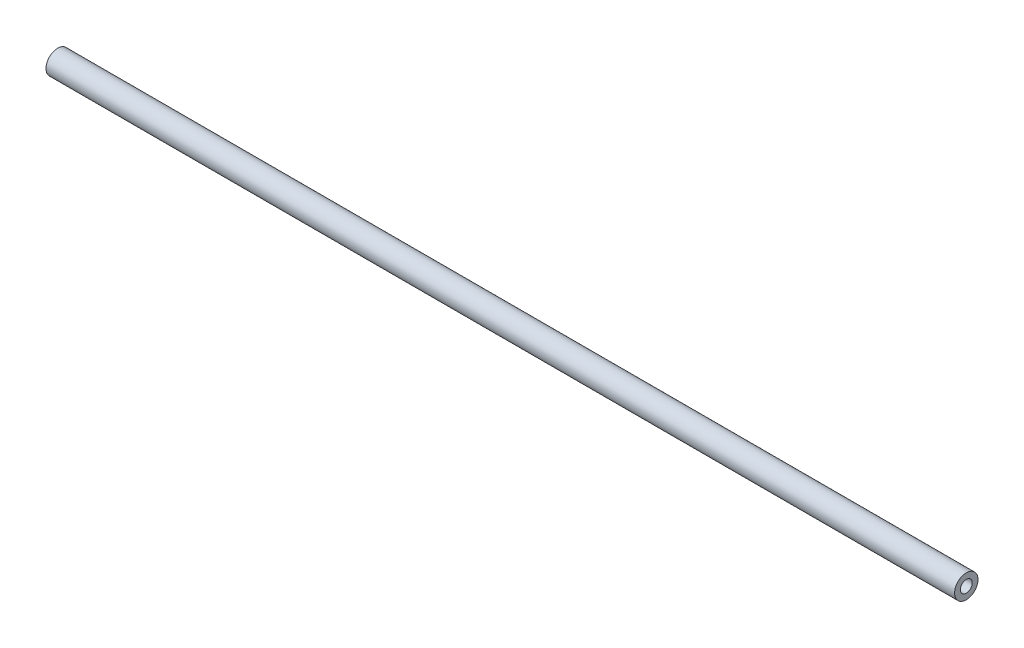
SolidWorks part; units mm, degrees
material "AISI 4340 Steel, normalized"
ref_plane "Front Plane" through (0, 0, 0) normal (0, 0, 1) x (1, 0, 0)
ref_plane "Top Plane" through (0, 0, 0) normal (0, 1, 0) x (1, 0, 0)
ref_plane "Right Plane" through (0, 0, 0) normal (1, 0, 0) x (0, 0, -1)
sketch "Sketch1" plane through (0, 0, 0) normal (1, 0, 0) x (0, 0, -1)
  circle A0 centre (0, 0) radius 3.9688
  dimension "D1" = 7.9375
extrude "Boss-Extrude1" add sketch "Sketch1" along normal mid plane 307.975
sketch "Sketch3" plane through (-153.9875, 0, 0) normal (-1, 0, 0) x (0, 0, 1)
  line L0 (0, 0) -> (0, -3.9688)
  circle A0 centre (0, 0) radius 3.9688 construction
hole_wizard "#10-32 Tapped Hole1" positions "3DSketch2" profile "Sketch6" tap size "#10-32" standard "ANSI Inch"
sketch3d "3DSketch2"
  point P0 (-153.9875, 0, 0)
sketch "Sketch6" plane through (-153.9875, 0, 0) normal (0, 1, 0) x (0, 0, 1)
  line L0 (0, 0) -> (0, 26.6133)
  line L1 (0, 26.6133) -> (2.0193, 25.4)
  line L2 (2.0193, 25.4) -> (2.0193, 0)
  line L5 (2.0193, 0) -> (0, 0)
  line L10 (0, 26.6133) -> (-2.0193, 25.4) construction
  line L11 (0, -6.35) -> (0, 107.95) construction
  dimension "Tap Drill Dia." = 4.0386
  dimension "Tap Drill Depth" = 25.4
  dimension "Drill Angle" = 118
cosmetic thread "Hole Thread1" parameters "D1"=3.048, "D2"=4.826
sketch "Sketch2" plane through (153.9875, 0, 0) normal (1, 0, 0) x (0, 0, -1)
  circle A0 centre (0, 0) radius 1.5558
  circle A1 centre (0, 0) radius 3.9688 construction
  dimension "D1" = 2.413
  dimension "D2" = 3.1115
extrude "Cut-Extrude1" cut sketch "Sketch2" against normal through all
mirror "Mirror1" about plane through (0, 0, 0) normal (1, 0, 0) of "#10-32 Tapped Hole1"
cosmetic thread "Hole Thread2" parameters "D1"=3.048, "D2"=4.826
